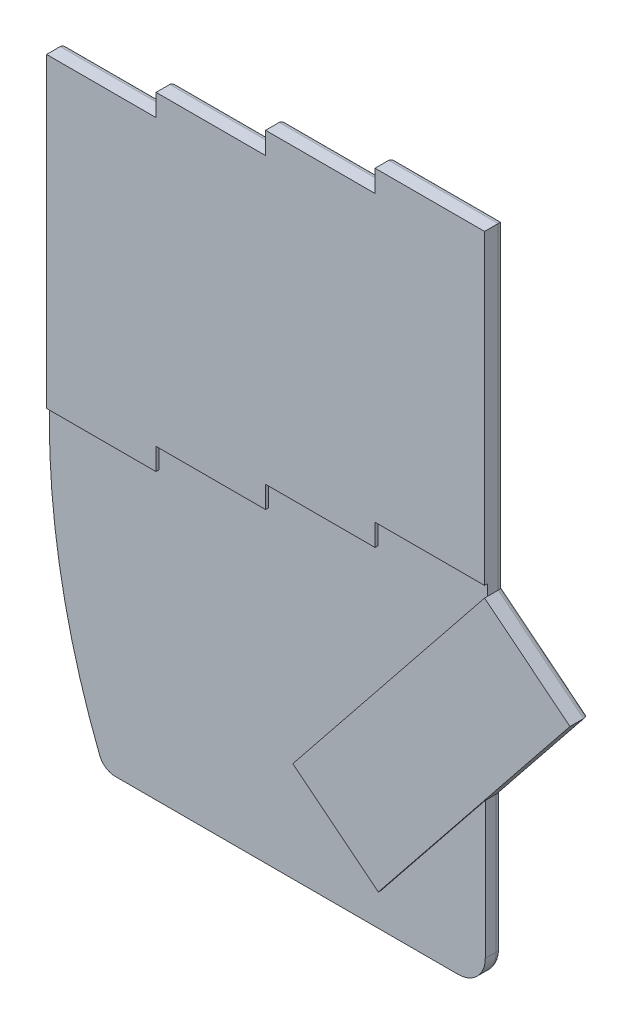
SolidWorks part; units mm, degrees
ref_plane "Front Plane" through (0, 0, 0) normal (0, 0, 1) x (1, 0, 0)
ref_plane "Top Plane" through (0, 0, 0) normal (0, 1, 0) x (1, 0, 0)
ref_plane "Right Plane" through (0, 0, 0) normal (1, 0, 0) x (0, 0, -1)
sketch "Sketch1" plane through (0, 0, 0) normal (0, 0, 1) x (1, 0, 0)
  line L0 (0.0888, 50.4455) -> (0.0888, 108.4455)
  line L26 (45.0813, 0) -> (12.0902, 0)
  line L59 (0.0888, 108.4455) -> (20.0888, 108.4455)
  line L60 (20.0888, 108.4455) -> (20.0888, 112.4455)
  line L61 (20.0888, 112.4455) -> (40.0888, 112.4455)
  line L62 (40.0888, 112.4455) -> (40.0888, 116.4455)
  line L63 (40.0888, 116.4455) -> (60.0888, 116.4455)
  line L64 (60.0888, 116.4455) -> (60.0888, 120.4455)
  line L68 (60.0888, 120.4455) -> (80.0888, 120.4455)
  line L70 (74.72, 0) -> (45.0813, 0)
  line L72 (80.0888, 62.4455) -> (80.0888, 120.4455)
  line L73 (80.0888, 62.4455) -> (95.6967, 49.9398)
  line L75 (95.6967, 49.9398) -> (79.72, 30)
  line L77 (79.72, 30) -> (79.72, 5)
  arc A1 (0.0888, 50.4455) -> (9.2995, 1.8991) centre (132.1238, 50.3497) ccw
  arc A2 (12.0902, 0) -> (9.2995, 1.8991) centre (12.0902, 3) cw
  arc A3 (79.72, 5) -> (74.72, 0) centre (74.72, 5) cw
  point P19 (79.72, 0)
  dimension "D3" = 20
  dimension "D6" = 50.4455
  dimension "D1" = 58
  dimension "D9" = 3
  dimension "D10" = 4
  dimension "D2" = 58
  dimension "D4" = 30
  dimension "D5" = 32.4455
  dimension "D7" = 70.4205
  dimension "D8" = 80
  dimension "D11" = 4
  dimension "D12" = 4
  dimension "D13" = 20
  dimension "D14" = 20
  dimension "D15" = 20
extrude "Boss-Extrude1" add sketch "Sketch1" against normal blind 3
sketch "Sketch2" plane through (0, 0, 0) normal (0, 0, 1) x (1, 0, 0)
  line L0 (20.0888, 108.4455) -> (20.0888, 52.4455)
  line L4 (0.0888, 50.4455) -> (0.0888, 108.4455)
  line L5 (0.0888, 108.4455) -> (20.0888, 108.4455)
  line L6 (20.0888, 52.4455) -> (0.0888, 52.4455)
extrude "Boss-Extrude2" add sketch "Sketch2" along normal blind 0.5
sketch "Sketch5" plane through (0, 0, 0) normal (0, 0, 1) x (1, 0, 0)
  line L1 (20.0888, 112.4455) -> (40.0888, 112.4455)
  line L2 (20.0888, 112.4455) -> (20.0888, 56.4455)
  line L3 (20.0888, 56.4455) -> (40.0888, 56.4455)
  line L4 (40.0888, 112.4455) -> (40.0888, 56.4455)
  dimension "D1" = 56
extrude "Boss-Extrude3" add sketch "Sketch5" along normal blind 0.5
sketch "Sketch6" plane through (0, 0, 0) normal (0, 0, 1) x (1, 0, 0)
  line L1 (40.0888, 116.4455) -> (60.0888, 116.4455)
  line L2 (40.0888, 116.4455) -> (40.0888, 60.4455)
  line L3 (40.0888, 60.4455) -> (60.0888, 60.4455)
  line L4 (60.0888, 116.4455) -> (60.0888, 60.4455)
  dimension "D1" = 56
extrude "Boss-Extrude4" add sketch "Sketch6" along normal blind 0.5
sketch "Sketch7" plane through (0, 0, 0) normal (0, 0, 1) x (1, 0, 0)
  line L0 (80.0888, 62.4455) -> (80.0888, 120.4455) construction
  line L1 (60.0888, 120.4455) -> (80.0888, 120.4455)
  line L2 (60.0888, 120.4455) -> (60.0888, 64.4455)
  line L3 (60.0888, 64.4455) -> (80.0888, 64.4455)
  line L4 (80.0888, 120.4455) -> (80.0888, 64.4455)
  dimension "D1" = 56
extrude "Boss-Extrude5" add sketch "Sketch7" along normal blind 0.5
sketch "Sketch10" plane through (0, 0, 0) normal (0, 0, 1) x (1, 0, 0)
  line L0 (80.0888, 62.4455) -> (95.6967, 49.9398)
  line L1 (80.0888, 62.4455) -> (45.0726, 18.7434)
  line L2 (95.6967, 49.9398) -> (60.6805, 6.2377)
  line L3 (45.0726, 18.7434) -> (60.6805, 6.2377)
  dimension "D1" = 56
extrude "Boss-Extrude18" add sketch "Sketch10" along normal blind 0.5
fillet "Fillet1" radius 1 16 edges at (87.7083, 39.9699, -3) (87.8927, 56.1926, -3) (80.0888, 91.4455, -3) (70.0888, 120.4455, -3) (60.0888, 118.4455, -3) (50.0888, 116.4455, -3) (40.0888, 114.4455, -3) (30.0888, 112.4455, -3) (20.0888, 110.4455, -3) (10.0888, 108.4455, -3) (0.0888, 79.4455, -3) (2.4029, 25.7376, -3) (10.4024, 0.5198, -3) (43.4051, 0, -3) (78.2555, 1.4645, -3) (79.72, 17.5, -3)
